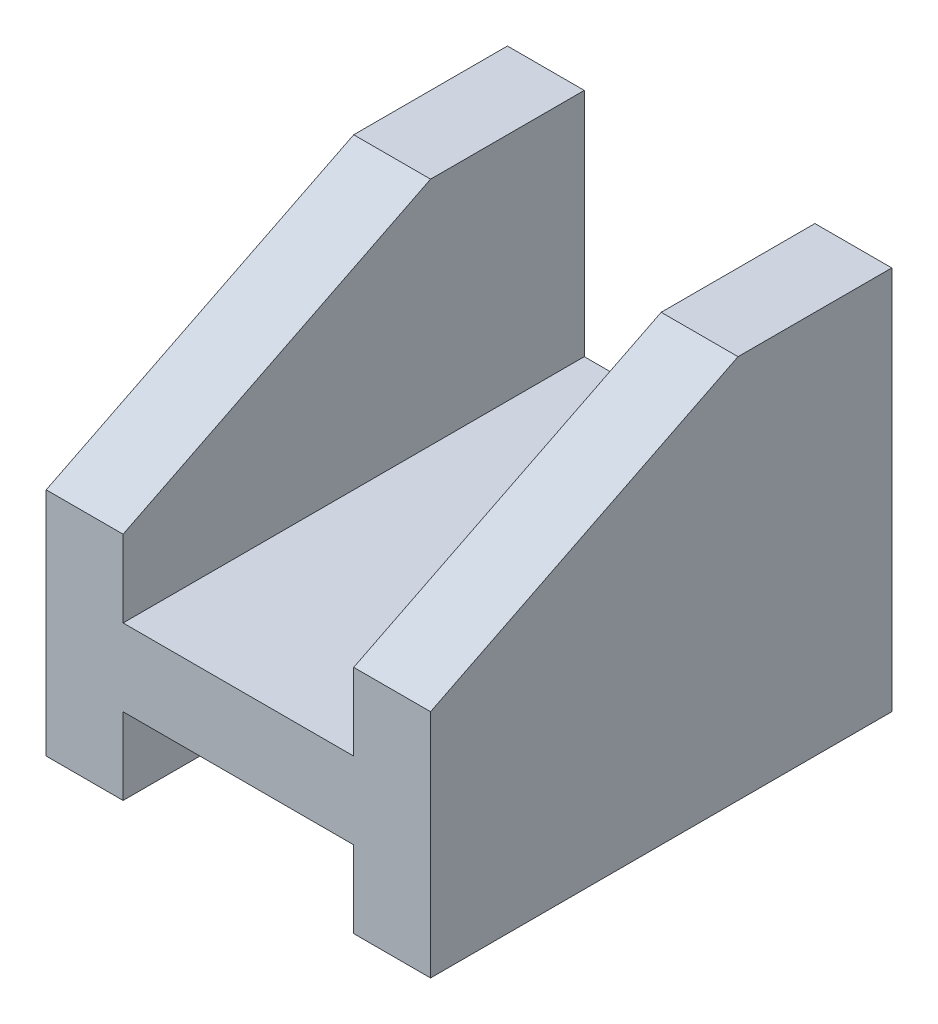
SolidWorks part; units mm, degrees
ref_plane "Front Plane" through (0, 0, 0) normal (0, 0, 1) x (1, 0, 0)
ref_plane "Top Plane" through (0, 0, 0) normal (0, 1, 0) x (1, 0, 0)
ref_plane "Right Plane" through (0, 0, 0) normal (1, 0, 0) x (0, 0, -1)
sketch "Sketch1" plane through (0, 0, 0) normal (0, 0, 1) x (1, 0, 0)
  line L0 (0, -10.7195) -> (0, -3.55) construction
  line L5 (9.525, 2.8) -> (-9.525, 2.8)
  line L6 (-9.525, 2.8) -> (-9.525, 21.85)
  line L7 (-9.525, 21.85) -> (-15.875, 21.85)
  line L8 (-15.875, 21.85) -> (-15.875, -9.9)
  line L9 (-15.875, -9.9) -> (-9.525, -9.9)
  line L12 (9.525, -3.55) -> (-9.525, -3.55)
  line L13 (-9.525, -3.55) -> (-9.525, -9.9)
  line L14 (9.525, -3.55) -> (9.525, -9.9)
  line L16 (15.875, -9.9) -> (9.525, -9.9)
  line L17 (15.875, 21.85) -> (15.875, -9.9)
  line L18 (9.525, 21.85) -> (15.875, 21.85)
  line L19 (9.525, 2.8) -> (9.525, 21.85)
  line L20 (0, 2.8) -> (0, 18.041) construction
  point P1 (0, 0)
  dimension "D1" = 12.7
  dimension "D2" = 31.75
  dimension "D3" = 6.35
  dimension "D4" = 6.35
  dimension "D5" = 31.75
extrude "Boss-Extrude1" add sketch "Sketch1" along normal blind 38.1
sketch "Sketch2" plane through (15.875, 0, 0) normal (1, 0, 0) x (0, 0, -1)
  line L0 (-38.1, 9.15) -> (-12.7, 21.85)
  line L1 (-38.1, -9.9) -> (-38.1, 21.85) construction
  line L2 (-38.1, 21.85) -> (0, 21.85) construction
  line L3 (-12.7, 21.85) -> (-38.1, 21.85)
  line L4 (-38.1, 21.85) -> (-38.1, 9.15)
  dimension "D1" = 12.7
  dimension "D2" = 25.4
extrude "Cut-Extrude1" cut sketch "Sketch2" against normal through all
